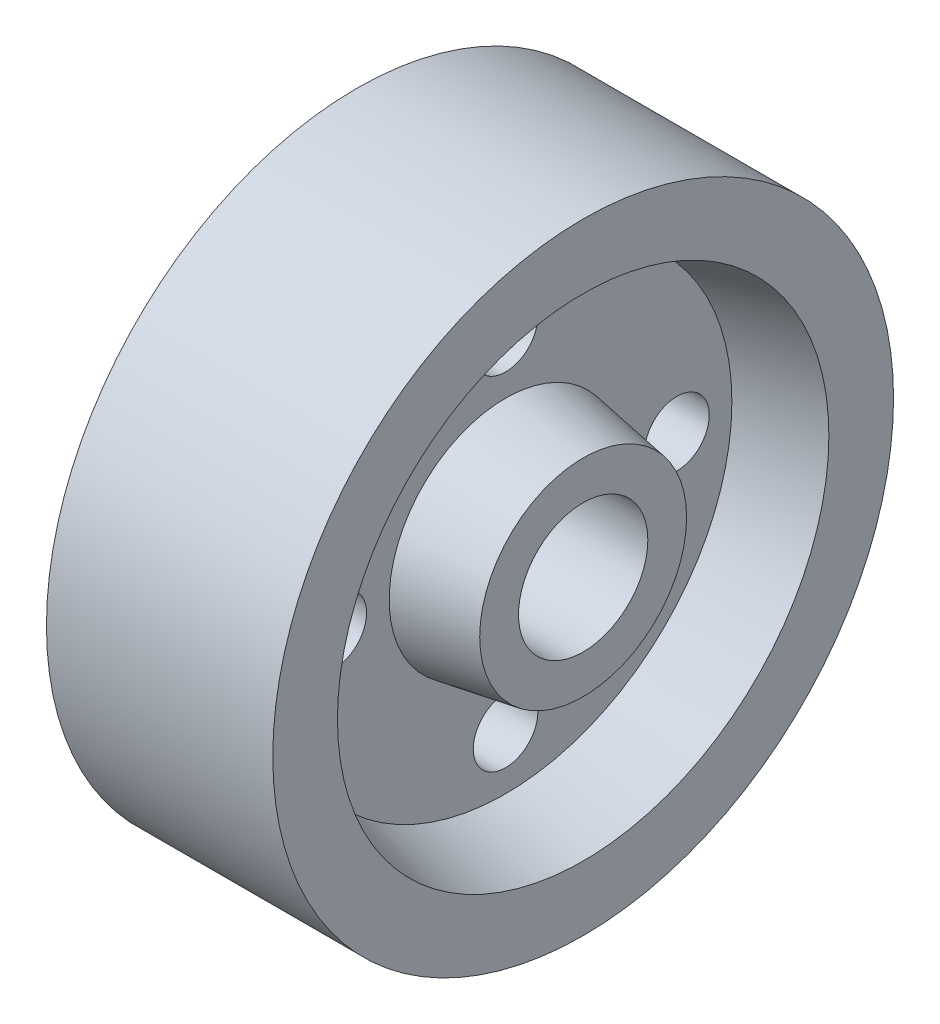
SolidWorks part; units mm, degrees
ref_plane "Front Plane" through (0, 0, 0) normal (0, 0, 1) x (1, 0, 0)
ref_plane "Top Plane" through (0, 0, 0) normal (0, 1, 0) x (1, 0, 0)
ref_plane "Right Plane" through (0, 0, 0) normal (1, 0, 0) x (0, 0, -1)
sketch "Sketch1" plane through (0, 0, 0) normal (0, 0, 1) x (1, 0, 0)
  line L4 (0, 0) -> (0, 10)
  line L6 (-12, 38) -> (-12, 48)
  line L7 (-12, 48) -> (23, 48)
  line L8 (23, 48) -> (23, 38)
  line L10 (11, 35) -> (11, 18)
  line L11 (11, 0) -> (0, 0)
  line L12 (23, 38) -> (11, 35)
  line L13 (-12, 38) -> (0, 35)
  line L14 (-22.1356, 14.6307) -> (-22.1356, 0) construction
  line L15 (-22.1356, 0) -> (51.2587, 0) construction
  line L16 (51.2587, 0) -> (51.2587, 12.9326) construction
  line L17 (11, 10) -> (23, 10)
  line L18 (23, 10) -> (23, 16)
  line L19 (23, 16) -> (11, 18)
  line L20 (5.5, 0) -> (5.5, 48) construction
  line L21 (0, 10) -> (-12, 10)
  line L22 (-12, 10) -> (-12, 16)
  line L23 (-12, 16) -> (0, 18)
  line L24 (0, 18) -> (0, 35)
  line L25 (11, 10) -> (11, 0)
  dimension "D1" = 35
  dimension "D2" = 11
  dimension "D3" = 10
  dimension "D4" = 38
  dimension "D5" = 48
  dimension "D6" = 35
  dimension "D7" = 35
  dimension "D8" = 104.036
  dimension "D9" = 6
  dimension "D10" = 12
  dimension "D11" = 18
  dimension "D12" = 10
  dimension "D13" = 6
  dimension "D14" = 18
  dimension "D15" = 12
revolve "Revolve5" add sketch "Sketch1" angle 360 about L11
sketch "Sketch15" plane through (11, 0, 0) normal (1, 0, 0) x (0, 0, -1)
  circle A0 centre (0, 0) radius 10
  dimension "D1" = 20
extrude "Cut-Extrude3" cut sketch "Sketch15" against normal blind 40.72
sketch "Sketch16" plane through (-12, 0, 0) normal (-1, 0, 0) x (0, 0, 1)
  circle A0 centre (0, 0) radius 26.5 construction
  circle A1 centre (0, 26.5) radius 5
  circle A3 centre (26.5, 0) radius 5
  circle A4 centre (0, -26.5) radius 5
  circle A5 centre (-26.5, 0) radius 5
  dimension "D1" = 53
  dimension "D2" = 10
  dimension "D3" = 4
extrude "Cut-Extrude4" cut sketch "Sketch16" against normal blind 40.72
